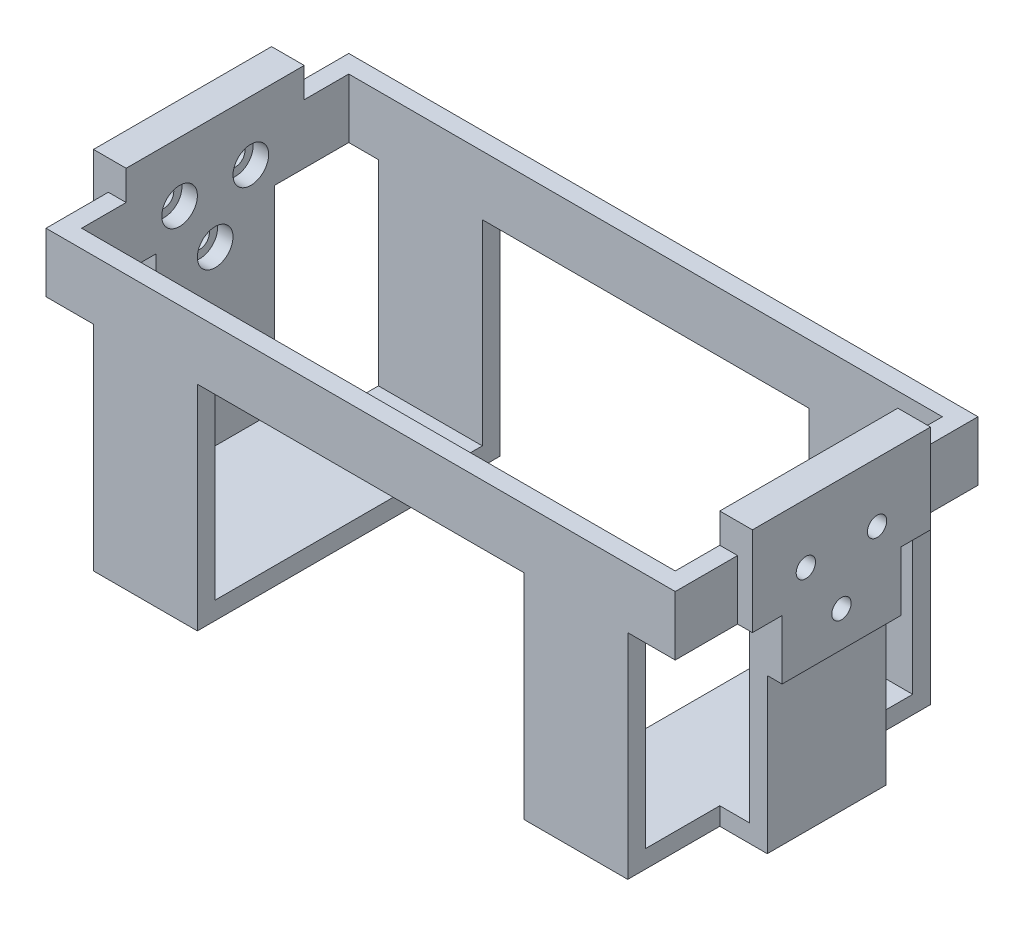
SolidWorks part; units mm, degrees
ref_plane "Спереди" through (0, 0, 0) normal (0, 0, 1) x (1, 0, 0)
ref_plane "Сверху" through (0, 0, 0) normal (0, 1, 0) x (1, 0, 0)
ref_plane "Справа" through (0, 0, 0) normal (1, 0, 0) x (0, 0, -1)
sketch "Эскиз1" plane through (0, 0, 0) normal (0, 1, 0) x (1, 0, 0)
  line L0 (-50, 10) -> (-50, -10) construction
  line L1 (50, 10) -> (50, -10) construction
  line L11 (0, 59.2084) -> (0, -58.6713) construction
  line L15 (27.5, 25.5) -> (45, 25.5)
  line L24 (45, 25.5) -> (45, 10)
  line L25 (45, 10) -> (53, 10)
  line L26 (53, 10) -> (53, -10)
  line L27 (53, -10) -> (45, -10)
  line L28 (45, -10) -> (45, -25.5)
  line L29 (45, -25.5) -> (27.5, -25.5)
  line L30 (27.5, -25.5) -> (27.5, 25.5)
  line L31 (27.5, 0) -> (-27.5, 0) construction
  line L32 (27.5, 22.5) -> (45, 22.5) construction
  line L33 (27.5, -22.5) -> (45, -22.5) construction
  line L34 (-27.5, -22.5) -> (-45, -22.5) construction
  line L35 (-27.5, 22.5) -> (-45, 22.5) construction
  line L36 (-27.5, -25.5) -> (-27.5, 25.5)
  line L37 (-45, -25.5) -> (-27.5, -25.5)
  line L38 (-45, -10) -> (-45, -25.5)
  line L39 (-53, -10) -> (-45, -10)
  line L40 (-53, 10) -> (-53, -10)
  line L41 (-45, 10) -> (-53, 10)
  line L42 (-45, 25.5) -> (-45, 10)
  line L43 (-27.5, 25.5) -> (-45, 25.5)
  dimension "D2" = 3
  dimension "D3" = 100
  dimension "D10" = 51
  dimension "D11" = 20
  dimension "D12" = 27.5
  dimension "D13" = 17.5
  dimension "D14" = 3
  dimension "D15" = 3
  dimension "D16" = 8
  dimension "D17" = 106
extrude "Бобышка-Вытянуть1" add sketch "Эскиз1" along normal blind 3
sketch "Эскиз2" plane through (0, 3, 0) normal (0, 1, 0) x (1, 0, 0)
  line L0 (-61.3503, 0) -> (73.9162, 0) construction
  line L1 (45, 10) -> (45, 25.5) construction
  line L2 (27.5, 25.5) -> (45, 25.5)
  line L3 (27.5, 25.5) -> (27.5, 22.5)
  line L4 (27.5, 22.5) -> (45, 22.5)
  line L5 (45, 25.5) -> (45, 22.5)
  line L6 (0, 35.6791) -> (0, -41.0709) construction
  line L7 (53, 10) -> (45, 10) construction
  line L8 (50, 10) -> (53, 10)
  line L9 (50, 10) -> (50, -10)
  line L10 (50, -10) -> (53, -10)
  line L11 (53, 10) -> (53, -10)
  line L12 (45, -25.5) -> (45, -22.5)
  line L13 (27.5, -22.5) -> (45, -22.5)
  line L14 (27.5, -25.5) -> (27.5, -22.5)
  line L15 (27.5, -25.5) -> (45, -25.5)
  line L16 (61.3503, 0) -> (-73.9162, 0) construction
  line L17 (-27.5, -25.5) -> (-45, -25.5)
  line L18 (-27.5, -25.5) -> (-27.5, -22.5)
  line L19 (-27.5, -22.5) -> (-45, -22.5)
  line L20 (-45, -25.5) -> (-45, -22.5)
  line L21 (-53, 10) -> (-53, -10)
  line L22 (-50, -10) -> (-53, -10)
  line L23 (-50, 10) -> (-50, -10)
  line L24 (-50, 10) -> (-53, 10)
  line L25 (-45, 25.5) -> (-45, 22.5)
  line L26 (-27.5, 22.5) -> (-45, 22.5)
  line L27 (-27.5, 25.5) -> (-27.5, 22.5)
  line L28 (-27.5, 25.5) -> (-45, 25.5)
  dimension "D1" = 3
extrude "Бобышка-Вытянуть2" add sketch "Эскиз2" along normal blind 43
sketch "Эскиз3" plane through (0, 46, 0) normal (0, 1, 0) x (1, 0, 0)
  line L0 (45, 25.5) -> (53, 25.5)
  line L1 (-27.5, 25.5) -> (27.5, 25.5)
  line L2 (-27.5, 25.5) -> (-27.5, 22.5)
  line L3 (-27.5, 22.5) -> (27.5, 22.5)
  line L4 (27.5, 25.5) -> (27.5, 22.5)
  line L5 (53, 25.5) -> (53, 10)
  line L6 (53, 10) -> (50, 10)
  line L7 (50, 10) -> (50, 22.5)
  line L8 (50, 22.5) -> (45, 22.5)
  line L9 (45, 22.5) -> (45, 25.5)
  line L10 (0, 35.4654) -> (0, -34.1197) construction
  line L11 (-58.6072, 0) -> (75.5319, 0) construction
  line L12 (-45, 22.5) -> (-45, 25.5)
  line L13 (-50, 22.5) -> (-45, 22.5)
  line L14 (-50, 10) -> (-50, 22.5)
  line L15 (-53, 10) -> (-50, 10)
  line L16 (-53, 25.5) -> (-53, 10)
  line L17 (-45, 25.5) -> (-53, 25.5)
  line L18 (58.6072, 0) -> (-75.5319, 0) construction
  line L19 (0, -35.4654) -> (0, 34.1197) construction
  line L20 (-45, -25.5) -> (-53, -25.5)
  line L21 (-53, -25.5) -> (-53, -10)
  line L22 (-53, -10) -> (-50, -10)
  line L23 (-50, -10) -> (-50, -22.5)
  line L24 (-50, -22.5) -> (-45, -22.5)
  line L25 (-45, -22.5) -> (-45, -25.5)
  line L26 (45, -22.5) -> (45, -25.5)
  line L27 (50, -22.5) -> (45, -22.5)
  line L28 (50, -10) -> (50, -22.5)
  line L29 (53, -10) -> (50, -10)
  line L30 (53, -25.5) -> (53, -10)
  line L31 (27.5, -25.5) -> (27.5, -22.5)
  line L32 (-27.5, -22.5) -> (27.5, -22.5)
  line L33 (-27.5, -25.5) -> (-27.5, -22.5)
  line L34 (-27.5, -25.5) -> (27.5, -25.5)
  line L35 (45, -25.5) -> (53, -25.5)
extrude "Бобышка-Вытянуть3" add sketch "Эскиз3" against normal blind 10
sketch "Эскиз4" plane through (-53, 0, 0) normal (-1, 0, 0) x (0, 0, 1)
  line L0 (-10, 36) -> (-10, 0) construction
  line L1 (-10, 26) -> (10, 26)
  line L2 (-10, 26) -> (-10, 36)
  line L3 (-15, 46) -> (15, 46)
  line L4 (10, 26) -> (10, 36)
  line L5 (-25.5, 46) -> (25.5, 46) construction
  line L11 (-10, 36) -> (-15, 36)
  line L12 (-15, 36) -> (-15, 46)
  line L14 (10, 36) -> (15, 36)
  line L16 (15, 36) -> (15, 46)
  line L18 (10, 36) -> (25.5, 36) construction
  line L19 (10, 36) -> (10, 0) construction
  dimension "D1" = 10
  dimension "D2" = 5
extrude "Бобышка-Вытянуть4" add sketch "Эскиз4" along normal blind 2.5
sketch "Эскиз5" plane through (-50, 0, 0) normal (1, 0, 0) x (0, 0, -1)
  line L1 (0, 46) -> (0, 3) construction
  line L3 (-25.5, 41) -> (22.5, 41) construction
  line L7 (-25.5, 46) -> (25.5, 46) construction
  line L8 (-25.5, 36) -> (-25.5, 46) construction
  circle A0 centre (-6, 41) radius 3
  circle A1 centre (0, 32) radius 3
  circle A2 centre (6, 41) radius 3
  dimension "D1" = 9
  dimension "D2" = 6
extrude "Вырез-Вытянуть1" cut sketch "Эскиз5" against normal blind 2.6
ref_point "Точка1"
ref_point "Точка2"
ref_point "Точка3"
sketch "Эскиз7" plane through (-52.6, 0, 0) normal (1, 0, 0) x (0, 0, -1)
  circle A0 centre (-6, 41) radius 1.625
  circle A1 centre (6, 41) radius 1.625
  circle A2 centre (0, 32) radius 1.625
  dimension "D1" = 3.25
extrude "Вырез-Вытянуть2" cut sketch "Эскиз7" against normal through all
ref_plane "Плоскость1" through (0, 0, 0) normal (1, 0, 0) x (0, 0, -1)
mirror "Зеркальное отражение2" about plane through (0, 0, 0) normal (1, 0, 0) of "Вырез-Вытянуть1", "Бобышка-Вытянуть4", "Вырез-Вытянуть2"
sketch "Эскиз8" plane through (0, 46, 0) normal (0, 1, 0) x (1, 0, 0)
  line L0 (-55.5, 15) -> (-55.5, -15)
  line L1 (-55.5, 15) -> (-50, 15)
  line L2 (-55.5, -15) -> (-50, -15)
  line L3 (-50, 15) -> (-50, -15)
  line L4 (55.5, 15) -> (55.5, -15)
  line L5 (55.5, 15) -> (50, 15)
  line L6 (55.5, -15) -> (50, -15)
  line L7 (50, 15) -> (50, -15)
  line L8 (50, 22.5) -> (50, -22.5) construction
  line L9 (-50, -10) -> (-50, 10) construction
extrude "Бобышка-Вытянуть5" add sketch "Эскиз8" along normal blind 5
